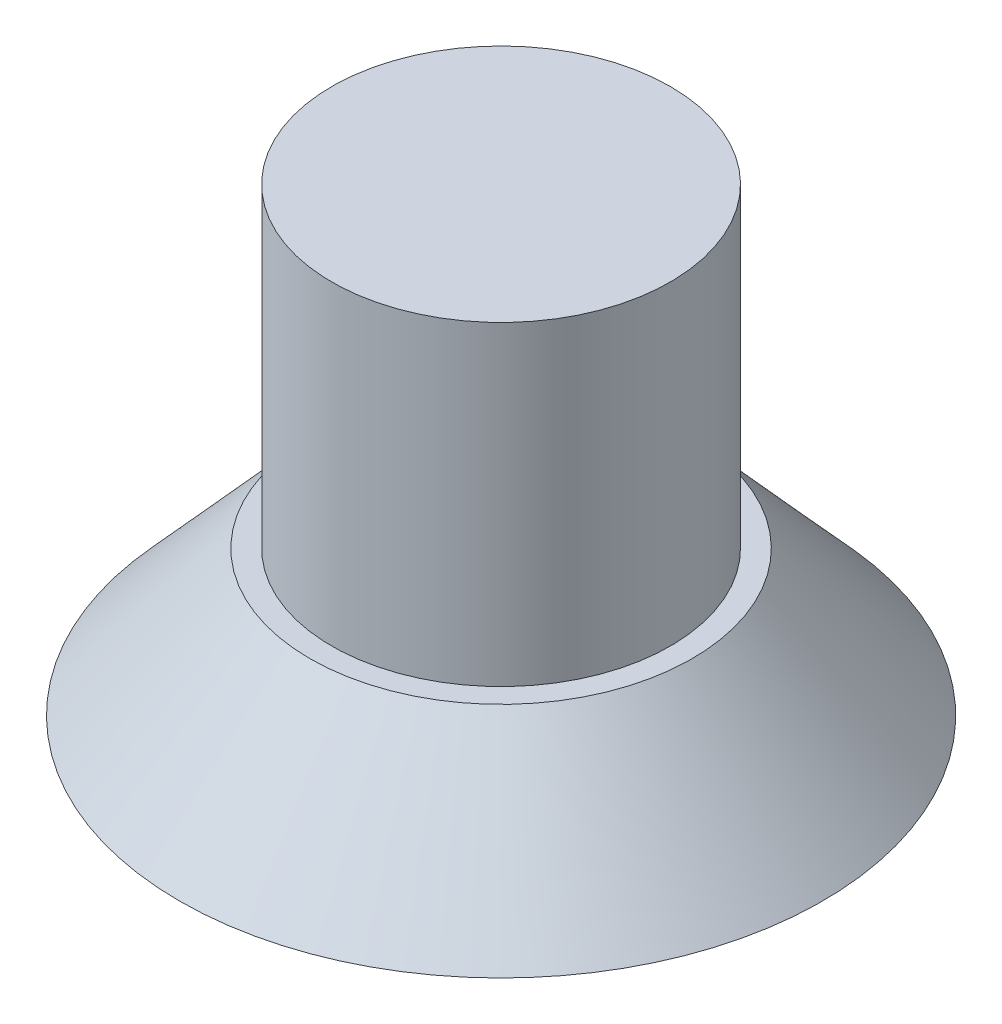
SolidWorks part; units mm, degrees
ref_plane "Front Plane" through (0, 0, 0) normal (0, 0, 1) x (1, 0, 0)
ref_plane "Top Plane" through (0, 0, 0) normal (0, 1, 0) x (1, 0, 0)
ref_plane "Right Plane" through (0, 0, 0) normal (1, 0, 0) x (0, 0, -1)
sketch "Sketch2" plane through (0, 0, 0) normal (0, 1, 0) x (1, 0, 0)
  line L0 (0, 3.612) -> (0, -4.8413) construction
  line L1 (-4.9449, 0) -> (6.0638, 0) construction
  circle A0 centre (0, 0) radius 3.3274
  dimension "D1" = 6.6548
extrude "Boss-Extrude1" add sketch "Sketch2" along normal blind 1.4986 draft 42
sketch "Sketch3" plane through (0, 1.4986, 0) normal (0, 1, 0) x (1, 0, 0)
  line L0 (0, 2.6249) -> (0, -3.7886) construction
  line L1 (-4.7843, 0) -> (5.0429, 0) construction
  circle A0 centre (0, 0) radius 1.7526
  dimension "D1" = 3.5052
extrude "Boss-Extrude2" add sketch "Sketch3" along normal blind 3.2639
cosmetic thread "Cosmetic Thread1" parameters "D1"=3.2639, "D2"=2.5603
